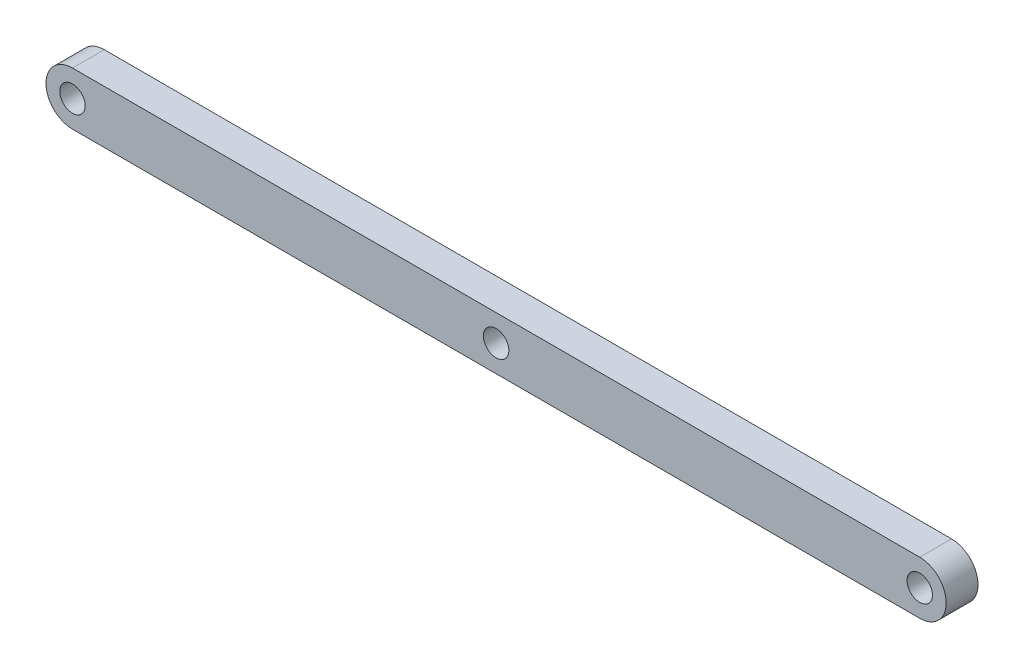
SolidWorks part; units mm, degrees
material "201 Annealed Stainless Steel (SS)"
ref_plane "Front Plane" through (0, 0, 0) normal (0, 0, 1) x (1, 0, 0)
ref_plane "Top Plane" through (0, 0, 0) normal (0, 1, 0) x (1, 0, 0)
ref_plane "Right Plane" through (0, 0, 0) normal (1, 0, 0) x (0, 0, -1)
sketch "Sketch1" plane through (0, 0, 0) normal (0, 0, 1) x (1, 0, 0)
  line L0 (0, 0) -> (800, 0) construction
  line L1 (0, 25) -> (800, 25)
  line L2 (0, -25) -> (800, -25)
  arc A0 (0, 25) -> (0, -25) centre (0, 0) ccw
  arc A1 (800, -25) -> (800, 25) centre (800, 0) ccw
  point P3 (400, 0)
  dimension "D1" = 800
  dimension "D2" = 50
extrude "Boss-Extrude2" add sketch "Sketch1" along normal blind 30 contours L1 A1 L2 A0
sketch "Sketch2" plane through (0, 0, 30) normal (0, 0, 1) x (1, 0, 0)
  line L0 (0, 0) -> (800, 0) construction
  point P0 (0, 0)
  point P3 (400, 0)
  point P6 (0, 0)
hole_wizard "Ø3.0mm Dowel Hole1" positions "3DSketch1" profile "Sketch4" hole size "Ø3.0" standard "ANSI Metric" end condition through all
sketch3d "3DSketch1"
  line L0 (800, 0, 30) -> (800, 0, 0) construction
  point P0 (0, 0, 30)
  point P4 (800, 0, 30)
  point P9 (400, 0, 30)
sketch "Sketch4" plane through (0, 0, 30) normal (1, 0, 0) x (0, -1, 0)
  line L0 (0, 0) -> (0, 30)
  line L1 (0, 30) -> (12, 30)
  line L2 (12, 30) -> (12, 0)
  line L5 (12, 0) -> (0, 0)
  line L11 (0, -6.35) -> (0, 107.95) construction
  dimension "Thru Hole Dia." = 24
  dimension "Thru Hole Depth" = 30
